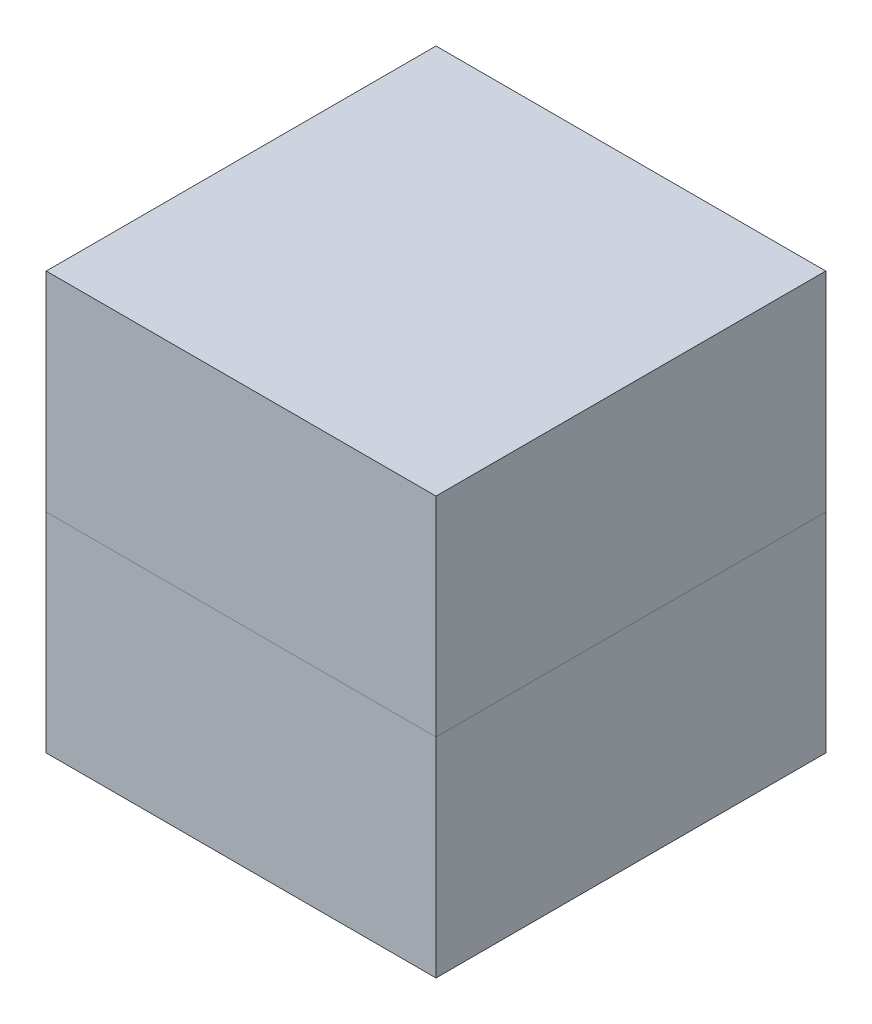
SolidWorks part; units mm, degrees
ref_plane "Front Plane" through (0, 0, 0) normal (0, 0, 1) x (1, 0, 0)
ref_plane "Top Plane" through (0, 0, 0) normal (0, 1, 0) x (1, 0, 0)
ref_plane "Right Plane" through (0, 0, 0) normal (1, 0, 0) x (0, 0, -1)
sketch "Sketch1" plane through (0, 0, 0) normal (0, 1, 0) x (1, 0, 0)
  line L1 (0, 1.302) -> (0, -1.4653) construction
  line L4 (-1.9685, 0) -> (-1.9685, 1.9685)
  line L5 (-1.9685, 1.9685) -> (1.9685, 1.9685)
  line L6 (1.9685, 0) -> (1.9685, 1.9685)
  line L8 (-1.9685, 0) -> (-1.9685, -1.9685)
  line L9 (-1.9685, -1.9685) -> (1.9685, -1.9685)
  line L10 (1.9685, 0) -> (1.9685, -1.9685)
  circle A0 centre (0, 0) radius 1.0541
  circle A1 centre (1.5113, 0) radius 0.4572
  circle A2 centre (0, 1.5113) radius 0.4572
  circle A3 centre (0, -1.5113) radius 0.4572
  circle A4 centre (-1.5113, 0) radius 0.4572
  dimension "D1" = 2.1082
  dimension "D2" = 0.9144
extrude "Boss-Extrude1" add sketch "Sketch1" along normal blind 5.08 contours L4 A4 A0 A2 L5 | A2 A0 A1 L6 L5 | A0 A3 L9 L10 A1 | A0 A4 L8 L9 A3
sketch "Sketch2" plane through (0, 5.08, 0) normal (0, 1, 0) x (1, 0, 0)
  line L3 (2.3721, -2.3721) -> (-2.3721, -2.3721)
  line L4 (2.3721, -2.3721) -> (2.3721, 2.3721)
  line L5 (2.3721, 2.3721) -> (-2.3721, 2.3721)
  line L6 (-2.3721, -2.3721) -> (-2.3721, 2.3721)
extrude "Boss-Extrude10" add sketch "Sketch2" against normal blind 2.54 separate body
sketch "Sketch3" plane through (0, 2.54, 0) normal (0, -1, 0) x (1, 0, 0)
  line L1 (-2.3721, 2.3721) -> (2.3721, 2.3721)
  line L2 (-2.3721, 2.3721) -> (-2.3721, -2.3721)
  line L3 (-2.3721, -2.3721) -> (2.3721, -2.3721)
  line L4 (2.3721, 2.3721) -> (2.3721, -2.3721)
  line L5 (-1.9685, 1.9685) -> (1.9685, 1.9685)
  line L6 (-1.9685, 1.9685) -> (-1.9685, -1.9685)
  line L7 (-1.9685, -1.9685) -> (1.9685, -1.9685)
  line L8 (1.9685, 1.9685) -> (1.9685, -1.9685)
extrude "Boss-Extrude13" add sketch "Sketch3" along normal blind 2.54 separate body
